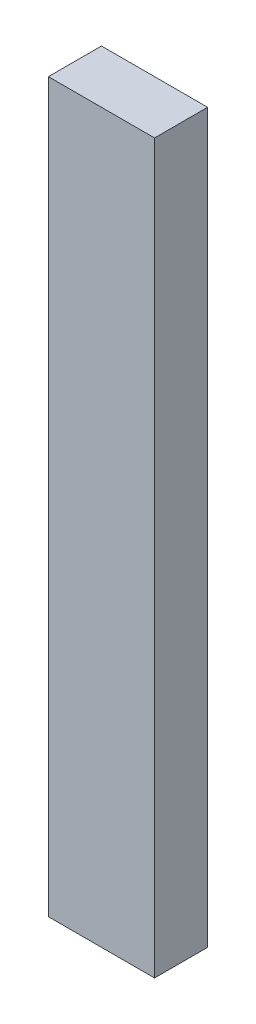
SolidWorks part; units mm, degrees
ref_plane "Front Plane" through (0, 0, 0) normal (0, 0, 1) x (1, 0, 0)
ref_plane "Top Plane" through (0, 0, 0) normal (0, 1, 0) x (1, 0, 0)
ref_plane "Right Plane" through (0, 0, 0) normal (1, 0, 0) x (0, 0, -1)
sketch "Sketch1" plane through (0, 0, 0) normal (0, 1, 0) x (1, 0, 0)
  line L1 (-304.8, 152.4) -> (304.8, 152.4)
  line L2 (-304.8, 152.4) -> (-304.8, -152.4)
  line L3 (-304.8, -152.4) -> (304.8, -152.4)
  line L4 (304.8, 152.4) -> (304.8, -152.4)
  line L5 (-304.8, 152.4) -> (304.8, -152.4) construction
  line L6 (-304.8, -152.4) -> (304.8, 152.4) construction
  point P0 (0, 0)
  dimension "D1" = 609.6
  dimension "D2" = 304.8
extrude "Boss-Extrude1" add sketch "Sketch1" along normal blind 4178.3
